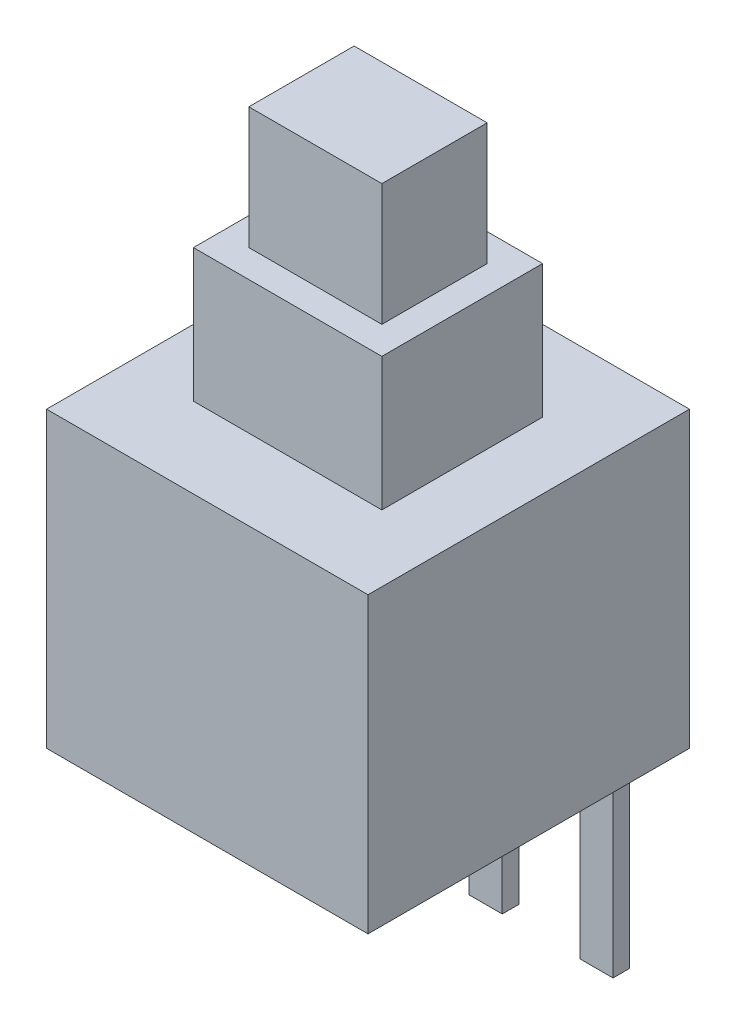
SolidWorks part; units mm, degrees
ref_plane "Plan de face" through (0, 0, 0) normal (0, 0, 1) x (1, 0, 0)
ref_plane "Plan de dessus" through (0, 0, 0) normal (0, 1, 0) x (1, 0, 0)
ref_plane "Plan de droite" through (0, 0, 0) normal (1, 0, 0) x (0, 0, -1)
sketch "Esquisse1" plane through (0, 0, 0) normal (0, 1, 0) x (1, 0, 0)
  line L1 (-2.9, 2.9) -> (2.9, 2.9)
  line L2 (-2.9, 2.9) -> (-2.9, -2.9)
  line L3 (-2.9, -2.9) -> (2.9, -2.9)
  line L4 (2.9, 2.9) -> (2.9, -2.9)
  line L5 (-2.9, 2.9) -> (2.9, -2.9) construction
  line L6 (-2.9, -2.9) -> (2.9, 2.9) construction
  point P0 (0, 0)
  dimension "D1" = 5.8
extrude "Boss.-Extru.1" add sketch "Esquisse1" along normal blind 5.3
sketch "Esquisse2" plane through (0, 5.3, 0) normal (0, 1, 0) x (1, 0, 0)
  line L1 (-1.7, 1.45) -> (1.7, 1.45)
  line L2 (-1.7, 1.45) -> (-1.7, -1.45)
  line L3 (-1.7, -1.45) -> (1.7, -1.45)
  line L4 (1.7, 1.45) -> (1.7, -1.45)
  line L5 (-1.7, 1.45) -> (1.7, -1.45) construction
  line L6 (-1.7, -1.45) -> (1.7, 1.45) construction
  point P0 (0, 0)
  dimension "D1" = 3.4
  dimension "D2" = 2.9
extrude "Boss.-Extru.2" add sketch "Esquisse2" along normal blind 2.4
sketch "Esquisse4" plane through (0, 7.7, 0) normal (0, 1, 0) x (1, 0, 0)
  line L9 (1.2, -0.95) -> (1.2, 0.95)
  line L10 (1.2, 0.95) -> (-1.2, 0.95)
  line L11 (-1.2, 0.95) -> (-1.2, -0.95)
  line L12 (-1.2, -0.95) -> (1.2, -0.95)
  line L13 (1.2, -0.95) -> (1.2, 0.95)
  line L14 (1.2, 0.95) -> (-1.2, 0.95)
  line L15 (-1.2, 0.95) -> (-1.2, -0.95)
  line L16 (-1.2, -0.95) -> (1.2, -0.95)
  dimension "D1" = 0.5
extrude "Boss.-Extru.3" add sketch "Esquisse4" along normal blind 2.2
sketch "Esquisse5" plane through (0, 0, 0) normal (0, -1, 0) x (1, 0, 0)
  line L1 (0.3, -2.4218) -> (-0.3, -2.4218)
  line L2 (0.3, -2.4218) -> (0.3, -2.1218)
  line L3 (0.3, -2.1218) -> (-0.3, -2.1218)
  line L4 (-0.3, -2.4218) -> (-0.3, -2.1218)
  line L5 (0.3, -2.4218) -> (-0.3, -2.1218) construction
  line L6 (0.3, -2.1218) -> (-0.3, -2.4218) construction
  line L7 (-1.7, -2.4218) -> (-2.3, -2.4218)
  line L8 (-1.7, -2.4218) -> (-1.7, -2.1218)
  line L9 (-1.7, -2.1218) -> (-2.3, -2.1218)
  line L10 (-2.3, -2.4218) -> (-2.3, -2.1218)
  line L11 (-1.7, -2.4218) -> (-2.3, -2.1218) construction
  line L12 (-1.7, -2.1218) -> (-2.3, -2.4218) construction
  line L13 (2.3, -2.4218) -> (1.7, -2.4218)
  line L14 (2.3, -2.4218) -> (2.3, -2.1218)
  line L15 (2.3, -2.1218) -> (1.7, -2.1218)
  line L16 (1.7, -2.4218) -> (1.7, -2.1218)
  line L17 (2.3, -2.4218) -> (1.7, -2.1218) construction
  line L18 (2.3, -2.1218) -> (1.7, -2.4218) construction
  point P0 (0, -2.2718)
  point P5 (-2, -2.2718)
  point P10 (2, -2.2718)
  dimension "D1" = 0.6
  dimension "D2" = 0.3
  dimension "D3" = 2
  dimension "D4" = 2
extrude "Boss.-Extru.4" add sketch "Esquisse5" along normal blind 3.5
